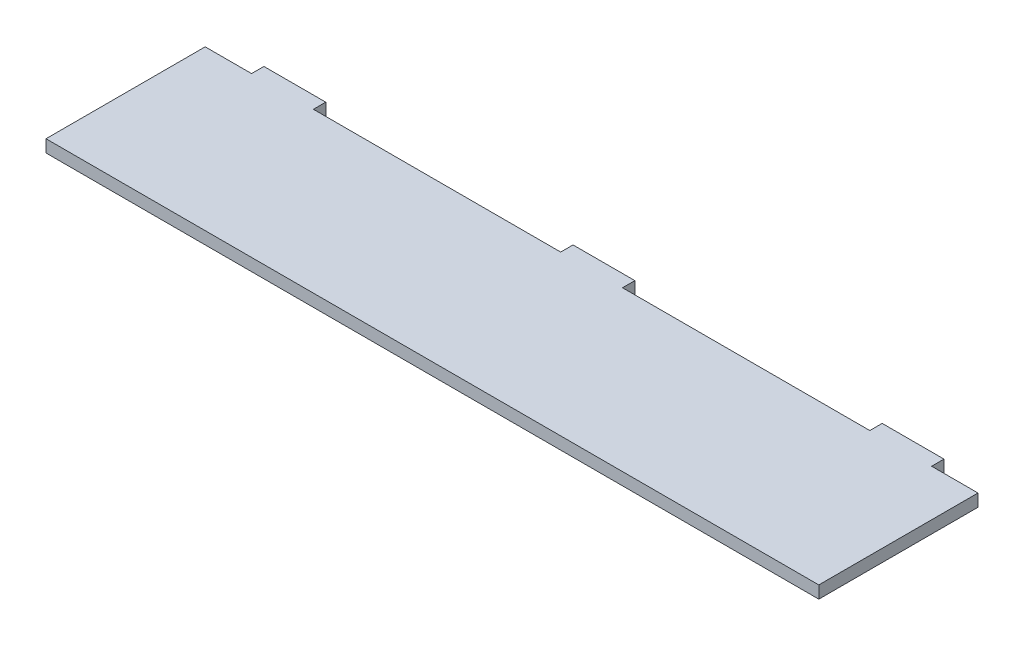
SolidWorks part; units mm, degrees
ref_plane "Front Plane" through (0, 0, 0) normal (0, 0, 1) x (1, 0, 0)
ref_plane "Top Plane" through (0, 0, 0) normal (0, 1, 0) x (1, 0, 0)
ref_plane "Right Plane" through (0, 0, 0) normal (1, 0, 0) x (0, 0, -1)
sketch "Sketch1" plane through (0, 0, 0) normal (0, 1, 0) x (1, 0, 0)
  line L0 (0, 27.75) -> (0, -57.6948) construction
  line L1 (-110, 27.75) -> (-90, 27.75)
  line L2 (-125, 23.75) -> (-125, -27.75)
  line L3 (-125, -27.75) -> (125, -27.75)
  line L5 (125, -27.75) -> (0, 0) construction
  line L6 (-125, -27.75) -> (0, 0) construction
  line L7 (-142.4824, 23.75) -> (142.4824, 23.75) construction
  line L8 (-110, 27.75) -> (-110, 23.75)
  line L9 (-90, 27.75) -> (-90, 23.75)
  line L10 (-110, 23.75) -> (-125, 23.75)
  line L11 (-90, 23.75) -> (-10, 23.75)
  line L12 (-10, 23.75) -> (-10, 27.75)
  line L13 (-10, 27.75) -> (10, 27.75)
  line L14 (10, 23.75) -> (10, 27.75)
  line L15 (90, 23.75) -> (10, 23.75)
  line L16 (110, 23.75) -> (125, 23.75)
  line L17 (90, 27.75) -> (90, 23.75)
  line L18 (110, 27.75) -> (110, 23.75)
  line L19 (125, 23.75) -> (125, -27.75)
  line L20 (110, 27.75) -> (90, 27.75)
  point P0 (0, 0)
  point P4 (0, 23.75)
  point P25 (0, -27.75)
  dimension "D1" = 250
  dimension "D2" = 55.5
  dimension "D3" = 8
  dimension "D4" = 20
  dimension "D5" = 10
  dimension "D6" = 4
  dimension "D7" = 80
extrude "Boss-Extrude1" add sketch "Sketch1" along normal blind 4
